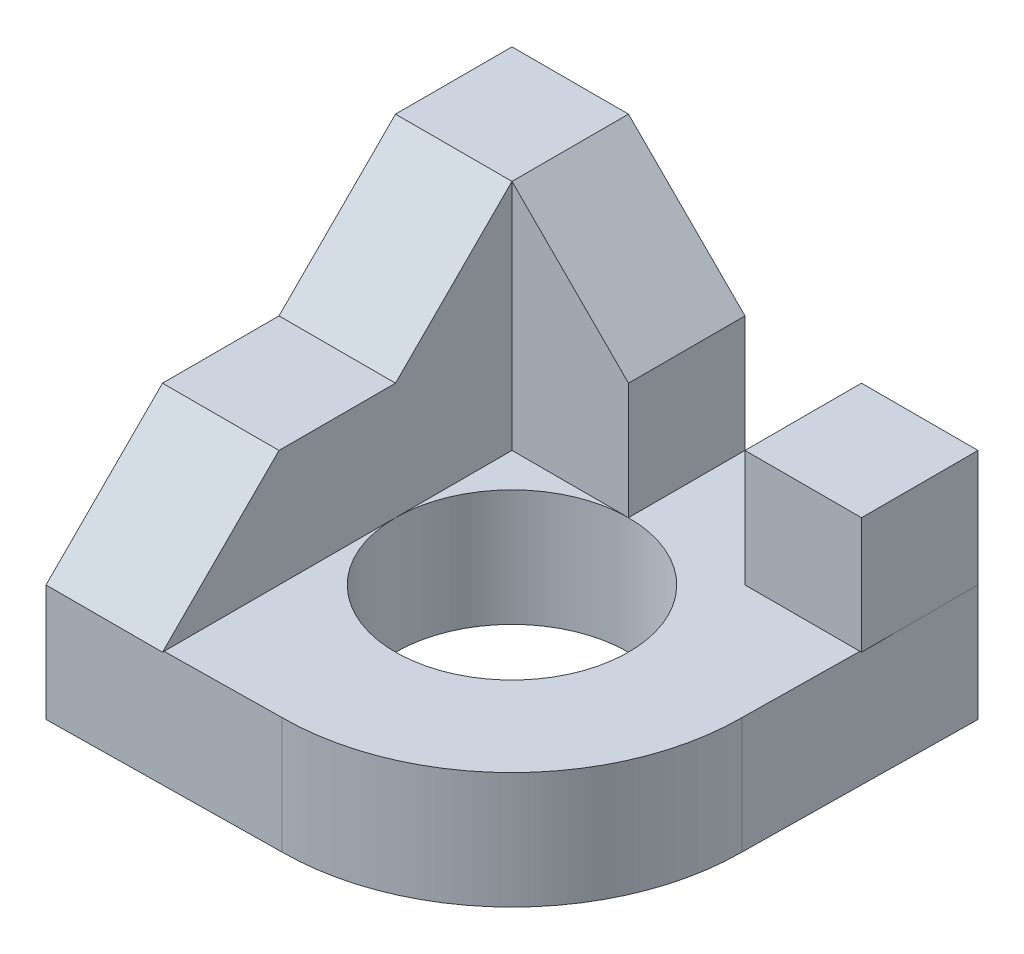
SolidWorks part; units mm, degrees
ref_plane "Front Plane" through (0, 0, 0) normal (0, 0, 1) x (1, 0, 0)
ref_plane "Top Plane" through (0, 0, 0) normal (0, 1, 0) x (1, 0, 0)
ref_plane "Right Plane" through (0, 0, 0) normal (1, 0, 0) x (0, 0, -1)
sketch "Sketch1" plane through (0, 0, 0) normal (0, 1, 0) x (1, 0, 0)
  line L0 (-27.9848, 21.2928) -> (-27.9848, -18.7072)
  line L1 (-27.9848, 21.2928) -> (12.0152, 21.2928)
  line L2 (12.0152, 21.2928) -> (11.744, 1.2928)
  line L3 (-7.9848, 21.2928) -> (-7.9848, 1.2928) construction
  line L5 (-27.9848, -18.7072) -> (-7.9848, -18.436)
  arc A0 (-7.9848, -18.436) -> (11.744, 1.2928) centre (-7.9848, 1.2928) ccw
  circle A1 centre (-7.9848, 1.2928) radius 10
  dimension "D3" = 20
  dimension "D1" = 40
  dimension "D2" = 40
extrude "Boss-Extrude1" add sketch "Sketch1" along normal blind 10
sketch "Sketch2" plane through (-27.9848, 0, 0) normal (-1, 0, 0) x (0, 0, 1)
  line L0 (18.7072, 10) -> (8.7072, 20)
  line L1 (8.7072, 20) -> (-1.2928, 20)
  line L2 (-1.2928, 20) -> (-11.2928, 30)
  line L3 (-11.2928, 30) -> (-21.2928, 30)
  line L4 (-21.2928, 30) -> (-21.2928, 10)
  line L5 (-21.2928, 10) -> (18.7072, 10)
  point P5 (0, 0)
  point P9 (0, 0)
  point P10 (0, 0)
  point P11 (0, 0)
  dimension "D1" = 10
  dimension "D2" = 20
  dimension "D3" = 10
  dimension "D4" = 10
  dimension "D5" = 10
extrude "Boss-Extrude2" add sketch "Sketch2" against normal blind 10 contours L2 L3 L4 L5 L0 L1
sketch "Sketch3" plane through (0, 0, -21.2928) normal (0, 0, -1) x (-1, 0, 0)
  line L0 (17.9848, 30) -> (17.9848, 10)
  line L1 (17.9848, 30) -> (17.9848, 10) construction
  line L2 (17.9848, 10) -> (7.9848, 10)
  line L3 (-12.0152, 10) -> (17.9848, 10) construction
  line L4 (7.9848, 10) -> (7.9848, 20)
  line L5 (7.9848, 20) -> (17.9848, 30)
  line L7 (-12.0152, 10) -> (-2.0152, 10)
  line L8 (-12.0152, 10) -> (-12.0152, 20)
  line L9 (-12.0152, 20) -> (-2.0152, 20)
  line L10 (-2.0152, 10) -> (-2.0152, 20)
  dimension "D1" = 10
  dimension "D2" = 10
  dimension "D3" = 10
  dimension "D4" = 10
extrude "Boss-Extrude3" add sketch "Sketch3" against normal blind 10
